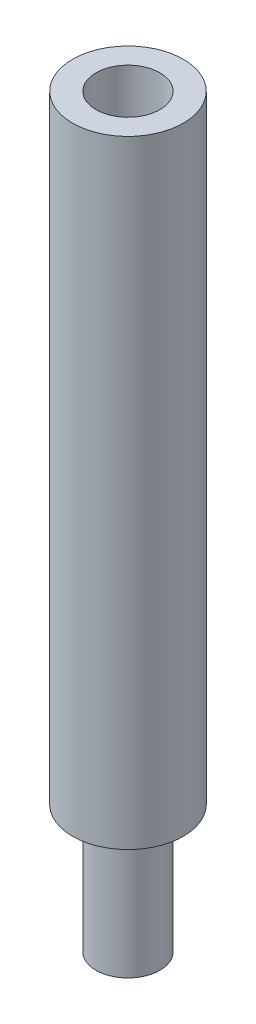
SolidWorks part; units mm, degrees
ref_plane "Front Plane" through (0, 0, 0) normal (0, 0, 1) x (1, 0, 0)
ref_plane "Top Plane" through (0, 0, 0) normal (0, 1, 0) x (1, 0, 0)
ref_plane "Right Plane" through (0, 0, 0) normal (1, 0, 0) x (0, 0, -1)
sketch "Sketch1" plane through (0, 0, 0) normal (1, 0, 0) x (0, 0, -1)
  line L0 (0, 27.5398) -> (0, -10.3672) construction
  line L1 (-2.6, 14.5) -> (-2.6, -14.5)
  line L2 (-2.6, -14.5) -> (-1.5, -14.5)
  line L3 (-1.5, -14.5) -> (-1.5, -20.5)
  line L4 (-1.5, -20.5) -> (0, -20.5)
  line L5 (-2.6, 14.5) -> (-1.5, 14.5)
  line L6 (-1.5, 14.5) -> (-1.5, 8.5)
  line L7 (-1.5, 8.5) -> (0, 8.5)
  line L8 (0, 8.5) -> (0, -20.5)
  point P13 (-2.6, 0)
  dimension "D1" = 5.2
  dimension "D2" = 3
  dimension "D3" = 6
  dimension "D4" = 6
  dimension "D5" = 29
revolve "Revolve1" add sketch "Sketch1" angle 360 about L0
